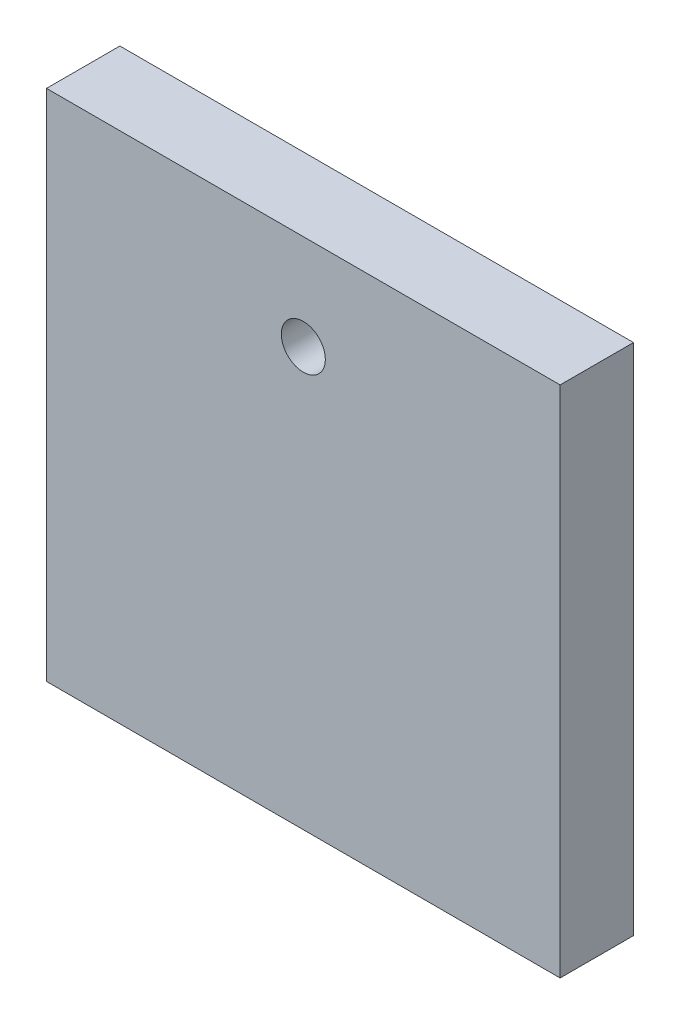
SolidWorks part; units mm, degrees
ref_plane "Front Plane" through (0, 0, 0) normal (0, 0, 1) x (1, 0, 0)
ref_plane "Top Plane" through (0, 0, 0) normal (0, 1, 0) x (1, 0, 0)
ref_plane "Right Plane" through (0, 0, 0) normal (1, 0, 0) x (0, 0, -1)
sketch "Sketch2" plane through (0, 0, 0) normal (0, 0, 1) x (1, 0, 0)
  line L1 (-17.5, -17.5) -> (17.5, -17.5)
  line L2 (-17.5, -17.5) -> (-17.5, 17.5)
  line L3 (-17.5, 17.5) -> (17.5, 17.5)
  line L4 (17.5, -17.5) -> (17.5, 17.5)
  line L5 (-17.5, -17.5) -> (17.5, 17.5) construction
  line L6 (-17.5, 17.5) -> (17.5, -17.5) construction
  point P0 (0, 0)
  dimension "D1" = 35
  dimension "D2" = 35
extrude "Boss-Extrude1" add sketch "Sketch2" along normal blind 5
sketch "Sketch3" plane through (0, 0, 5) normal (0, 0, 1) x (1, 0, 0)
  line L0 (0, -17.5) -> (0, -7.5) construction
  line L1 (-17.5, -17.5) -> (17.5, -17.5) construction
  line L2 (0, -7.5) -> (0, 11) construction
  circle A0 centre (0, 11) radius 1.5
  dimension "D3" = 3
  dimension "D1" = 10
  dimension "D2" = 18.5
extrude "Cut-Extrude1" cut sketch "Sketch3" against normal through all and the other way through all
